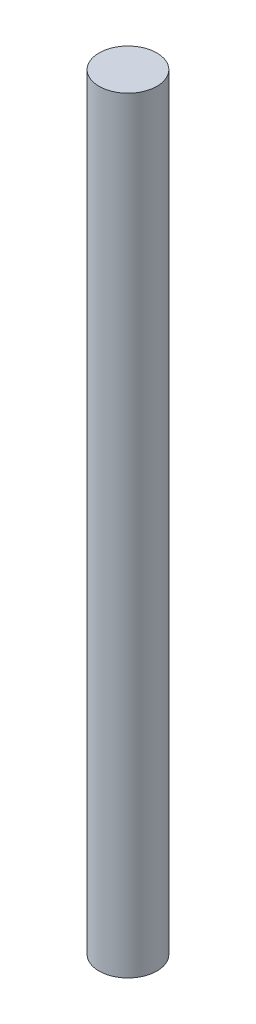
SolidWorks part; units mm, degrees
ref_plane "前视基准面" through (0, 0, 0) normal (0, 0, 1) x (1, 0, 0)
ref_plane "上视基准面" through (0, 0, 0) normal (0, 1, 0) x (1, 0, 0)
ref_plane "右视基准面" through (0, 0, 0) normal (1, 0, 0) x (0, 0, -1)
sketch "草图1" plane through (0, 0, 0) normal (0, 1, 0) x (1, 0, 0)
  circle A0 centre (0, 0) radius 4
  dimension "D1" = 8
extrude "凸台-拉伸1" add sketch "草图1" along normal blind 106
